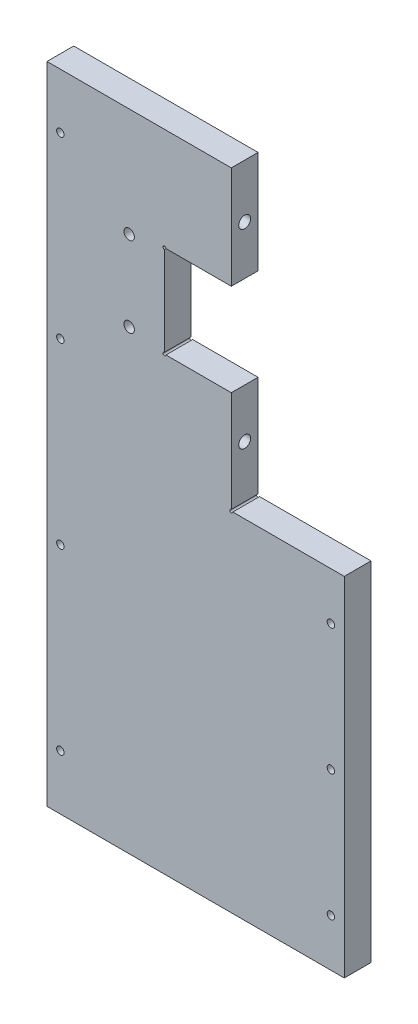
SolidWorks part; units mm, degrees
ref_plane "Front Plane" through (0, 0, 0) normal (0, 0, 1) x (1, 0, 0)
ref_plane "Top Plane" through (0, 0, 0) normal (0, 1, 0) x (1, 0, 0)
ref_plane "Right Plane" through (0, 0, 0) normal (1, 0, 0) x (0, 0, -1)
sketch "Sketch1" plane through (0, 0, 0) normal (0, 0, 1) x (1, 0, 0)
  line L0 (200, 234) -> (124, 234)
  line L1 (0, 0) -> (200, 0)
  line L2 (0, 0) -> (0, 434)
  line L3 (124, 434) -> (124, 365)
  line L4 (200, 0) -> (200, 234)
  line L5 (124, 434) -> (0, 434)
  line L6 (124, 365) -> (79, 365)
  line L7 (79, 365) -> (79, 303)
  line L8 (79, 303) -> (124, 303)
  line L9 (124, 303) -> (124, 234)
  dimension "D1" = 200
  dimension "D2" = 234
  dimension "D3" = 124
  dimension "D4" = 434
  dimension "D5" = 69
  dimension "D6" = 69
  dimension "D7" = 45
  dimension "D8" = 124
extrude "Boss-Extrude1" add sketch "Sketch1" along normal blind 18
sketch "Sketch2" plane through (0, 0, 18) normal (0, 0, 1) x (1, 0, 0)
  circle A0 centre (79, 365) radius 1
  circle A1 centre (79, 303) radius 1
  circle A2 centre (124, 234) radius 1
  dimension "D1" = 2
  dimension "D2" = 2
  dimension "D3" = 2
extrude "Cut-Extrude1" cut sketch "Sketch2" against normal blind 18
hole_wizard "Ø5.0 (5) Diameter Hole1" positions "Sketch4" profile "Sketch3" hole size "Ø5.0" standard "ISO" end condition through all
sketch "Sketch4" plane through (0, 0, 18) normal (0, 0, 1) x (1, 0, 0)
  line L0 (0, 434) -> (0, 0) construction
  line L1 (0, 0) -> (200, 0) construction
  point P0 (9, 397)
  point P2 (9, 277)
  point P4 (9, 157)
  point P6 (9, 37)
  dimension "D1" = 9
  dimension "D2" = 9
  dimension "D3" = 9
  dimension "D4" = 9
  dimension "D5" = 120
  dimension "D6" = 120
  dimension "D7" = 120
  dimension "D8" = 37
sketch "Sketch3" plane through (9, 397, 18) normal (1, 0, 0) x (0, -1, 0)
  line L0 (0, 0) -> (0, 18)
  line L1 (0, 18) -> (2.5, 18)
  line L2 (2.5, 18) -> (2.5, 0)
  line L5 (2.5, 0) -> (0, 0)
  line L11 (0, -6.35) -> (0, 107.95) construction
  dimension "Thru Hole Dia." = 5
  dimension "Thru Hole Depth" = 18
hole_wizard "Ø5.0 (5) Diameter Hole2" positions "Sketch6" profile "Sketch5" hole size "Ø5.0" standard "ISO" end condition through all
sketch "Sketch6" plane through (0, 0, 0) normal (0, 0, -1) x (-1, 0, 0)
  line L0 (-200, 0) -> (-200, 234) construction
  line L1 (-200, 234) -> (-125, 234) construction
  point P0 (-191, 202)
  point P2 (-191, 117)
  point P4 (-191, 32)
  dimension "D1" = 9
  dimension "D2" = 9
  dimension "D3" = 9
  dimension "D4" = 85
  dimension "D5" = 85
  dimension "D6" = 32
sketch "Sketch5" plane through (191, 202, 0) normal (1, 0, 0) x (0, 1, 0)
  line L0 (0, 0) -> (0, 18)
  line L1 (0, 18) -> (2.5, 18)
  line L2 (2.5, 18) -> (2.5, 0)
  line L5 (2.5, 0) -> (0, 0)
  line L11 (0, -6.35) -> (0, 107.95) construction
  dimension "Thru Hole Dia." = 5
  dimension "Thru Hole Depth" = 18
hole_wizard "Ø8.0 (8) Diameter Hole1" positions "Sketch8" profile "Sketch7" hole size "Ø8.0" standard "ISO"
sketch "Sketch8" plane through (124, 0, 0) normal (1, 0, 0) x (0, 0, -1)
  point P0 (-9, 398)
  point P3 (-9, 270)
sketch "Sketch7" plane through (124, 398, 9) normal (0, 1, 0) x (0, 0, -1)
  line L0 (0, 0) -> (0, 26)
  line L1 (0, 26) -> (4, 26)
  line L2 (4, 26) -> (4, 0)
  line L5 (4, 0) -> (0, 0)
  line L10 (0, 26) -> (-4, 26) construction
  line L11 (0, -6.35) -> (0, 107.95) construction
  dimension "Hole Dia." = 8
  dimension "Hole Depth" = 26
  dimension "Drill Angle" = 180
hole_wizard "Ø7.0 (7) Diameter Hole1" positions "Sketch10" profile "Sketch9" hole size "Ø7.0" standard "ISO" end condition through all
sketch "Sketch10" plane through (0, 0, 18) normal (0, 0, 1) x (1, 0, 0)
  line L0 (124, 434) -> (0, 434) construction
  point P0 (55.2879, 361)
  point P2 (55.2879, 307)
  dimension "D1" = 54
  dimension "D2" = 73
sketch "Sketch9" plane through (55.2879, 361, 18) normal (1, 0, 0) x (0, -1, 0)
  line L0 (0, 0) -> (0, 18)
  line L1 (0, 18) -> (3.5, 18)
  line L2 (3.5, 18) -> (3.5, 0)
  line L5 (3.5, 0) -> (0, 0)
  line L11 (0, -6.35) -> (0, 107.95) construction
  dimension "Thru Hole Dia." = 7
  dimension "Thru Hole Depth" = 18
